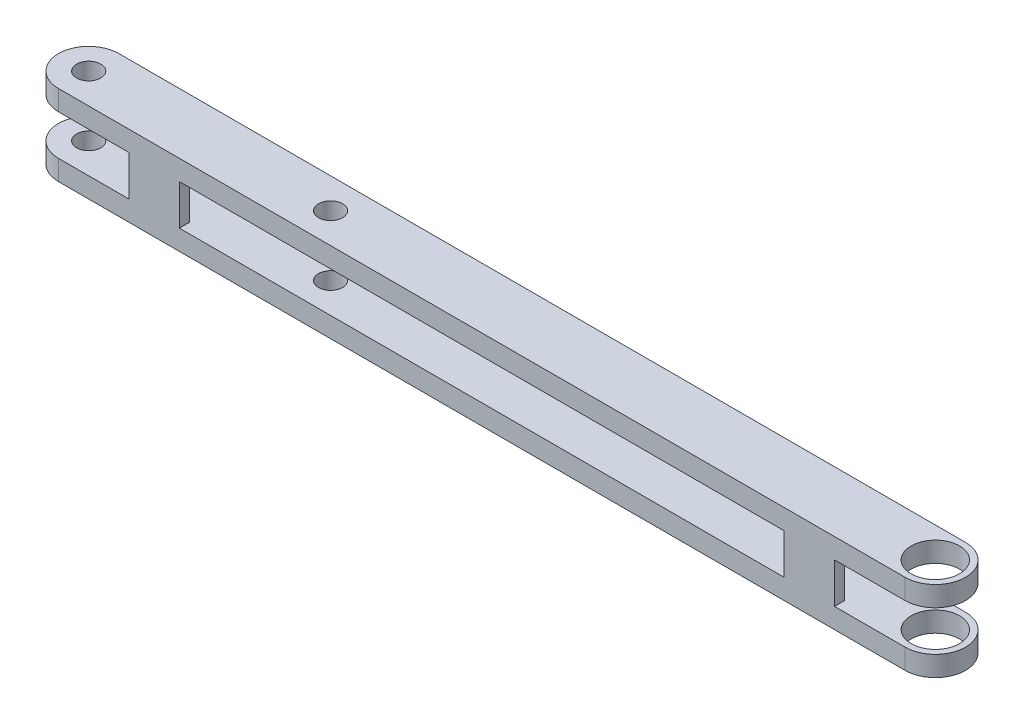
SolidWorks part; units mm, degrees
ref_plane "前视基准面" through (0, 0, 0) normal (0, 0, 1) x (1, 0, 0)
ref_plane "上视基准面" through (0, 0, 0) normal (0, 1, 0) x (1, 0, 0)
ref_plane "右视基准面" through (0, 0, 0) normal (1, 0, 0) x (0, 0, -1)
sketch "草图1" plane through (0, 0, 0) normal (0, 1, 0) x (1, 0, 0)
  line L0 (-105, 0) -> (105, 0) construction
  line L1 (-105, 7.5) -> (105, 7.5)
  line L2 (-105, -7.5) -> (105, -7.5)
  arc A0 (-105, 7.5) -> (-105, -7.5) centre (-105, 0) ccw
  arc A1 (105, -7.5) -> (105, 7.5) centre (105, 0) ccw
  point P3 (0, 0)
  dimension "D1" = 210
  dimension "D2" = 15
extrude "凸台-拉伸1" add sketch "草图1" along normal blind 20
sketch "草图2" plane through (0, 0, -7.5) normal (0, 0, -1) x (-1, 0, 0)
  line L0 (0, 0) -> (0, 10) construction
  line L1 (75, 5) -> (-75, 5)
  line L2 (75, 5) -> (75, 15)
  line L3 (75, 15) -> (-75, 15)
  line L4 (-75, 5) -> (-75, 15)
  line L5 (75, 5) -> (-75, 15) construction
  line L6 (75, 15) -> (-75, 5) construction
  line L7 (-105, 0) -> (105, 0) construction
  point P0 (0, 10)
  dimension "D1" = 10
  dimension "D2" = 10
  dimension "D3" = 150
extrude "切除-拉伸3" cut sketch "草图2" against normal through all
sketch "草图3" plane through (0, 0, -7.5) normal (0, 0, -1) x (-1, 0, 0)
  line L0 (-75, 5) -> (75, 5) construction
  line L1 (112.5, 15) -> (87.5, 15)
  line L2 (112.5, 15) -> (112.5, 5)
  line L3 (112.5, 5) -> (87.5, 5)
  line L4 (87.5, 15) -> (87.5, 5)
  line L5 (75, 15) -> (-75, 15) construction
  line L6 (112.5, 0) -> (112.5, 20) construction
  line L7 (0, 0) -> (0, 43.872) construction
  line L8 (-105, 0) -> (105, 0) construction
  line L9 (-87.5, 15) -> (-87.5, 5)
  line L10 (-112.5, 5) -> (-87.5, 5)
  line L11 (-112.5, 15) -> (-112.5, 5)
  line L12 (-112.5, 15) -> (-87.5, 15)
  dimension "D1" = 25
extrude "切除-拉伸4" cut sketch "草图3" against normal through all
sketch "草图4" plane through (-87.5, 0, 0) normal (-1, 0, 0) x (0, 0, 1)
  line L0 (7.5, 5) -> (-7.5, 5) construction
  line L1 (5, 15) -> (-5, 15)
  line L2 (5, 15) -> (5, 5)
  line L3 (5, 5) -> (-5, 5)
  line L4 (-5, 15) -> (-5, 5)
  line L5 (5, 15) -> (-5, 5) construction
  line L6 (5, 5) -> (-5, 15) construction
  line L7 (0, 0) -> (0, 10) construction
  line L8 (7.5, 15) -> (-7.5, 15) construction
  point P0 (0, 10)
  dimension "D1" = 10
extrude "切除-拉伸5" cut sketch "草图4" against normal through all
sketch "草图5" plane through (0, 20, 0) normal (0, 1, 0) x (1, 0, 0)
  line L0 (-105, 0) -> (0, 0) construction
  line L1 (0, 0) -> (105, 0) construction
  circle A0 centre (-105, 0) radius 3
  circle A1 centre (105, 0) radius 6
  dimension "D1" = 6
  dimension "D2" = 12
  dimension "D3" = 105
  dimension "D4" = 105
extrude "切除-拉伸6" cut sketch "草图5" against normal through all
sketch "草图6" plane through (0, 20, 0) normal (0, 1, 0) x (1, 0, 0)
  line L0 (-45, 0) -> (0, 0) construction
  circle A0 centre (-45, 0) radius 3
  circle A1 centre (-105, 0) radius 5 construction
  dimension "D2" = 6
  dimension "D1" = 60
extrude "切除-拉伸7" cut sketch "草图6" against normal through all
